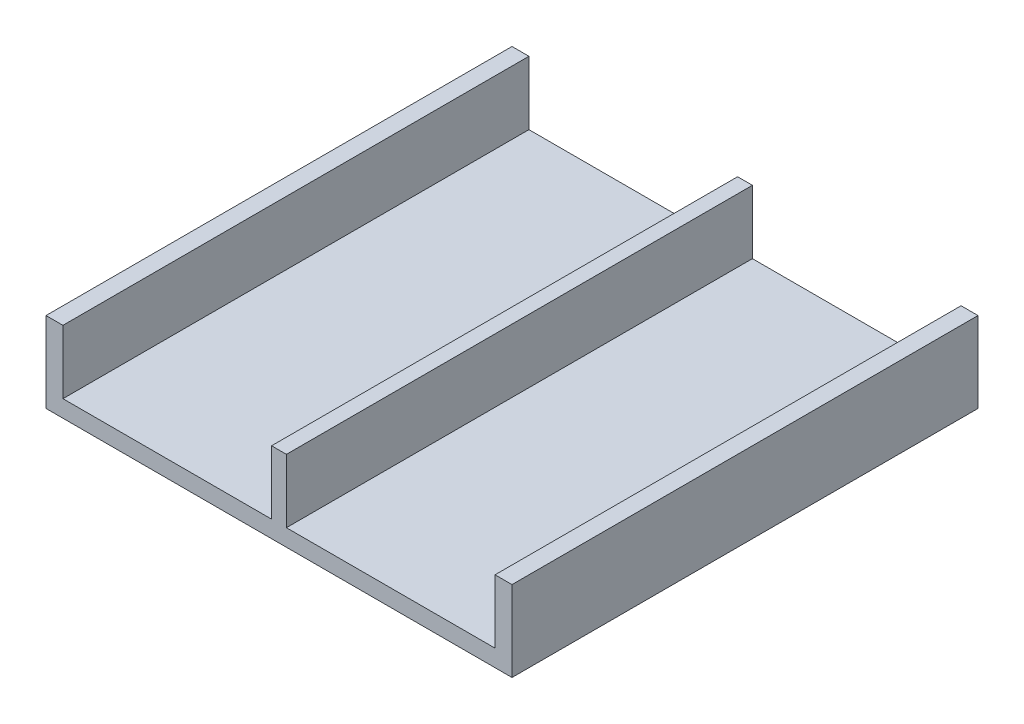
SolidWorks part; units mm, degrees
ref_plane "Front Plane" through (0, 0, 0) normal (0, 0, 1) x (1, 0, 0)
ref_plane "Top Plane" through (0, 0, 0) normal (0, 1, 0) x (1, 0, 0)
ref_plane "Right Plane" through (0, 0, 0) normal (1, 0, 0) x (0, 0, -1)
sketch "Sketch1" plane through (0, 0, 0) normal (0, 1, 0) x (1, 0, 0)
  line L1 (-55, 55) -> (55, 55)
  line L2 (-55, 55) -> (-55, -55)
  line L3 (-55, -55) -> (55, -55)
  line L4 (55, 55) -> (55, -55)
  line L5 (-55, 55) -> (55, -55) construction
  line L6 (-55, -55) -> (55, 55) construction
  point P0 (0, 0)
  dimension "D1" = 110
  dimension "D2" = 110
extrude "Boss-Extrude1" add sketch "Sketch1" along normal blind 19
sketch "Sketch2" plane through (0, 19, 0) normal (0, 1, 0) x (1, 0, 0)
  line L0 (0, 55) -> (0, -55) construction
  line L1 (55, 55) -> (-55, 55) construction
  line L2 (-55, -55) -> (55, -55) construction
  line L3 (-1.75, 55) -> (-1.75, -55) construction
  line L4 (1.75, 55) -> (1.75, -55) construction
  line L5 (-51, 55) -> (-51, -55) construction
  line L6 (-55, 55) -> (-55, -55) construction
  line L7 (51, 55) -> (51, -55) construction
  line L8 (-51, 55) -> (-1.75, 55)
  line L9 (-51, 55) -> (-51, -55)
  line L10 (-51, -55) -> (-1.75, -55)
  line L11 (-1.75, 55) -> (-1.75, -55)
  line L12 (55, -55) -> (55, 55) construction
  line L14 (1.75, 55) -> (51, 55)
  line L15 (1.75, 55) -> (1.75, -55)
  line L16 (1.75, -55) -> (51, -55)
  line L17 (51, 55) -> (51, -55)
  dimension "D1" = 1.75
  dimension "D2" = 1.75
  dimension "D3" = 4
  dimension "D4" = 4
extrude "Cut-Extrude2" cut sketch "Sketch2" against normal blind 15
